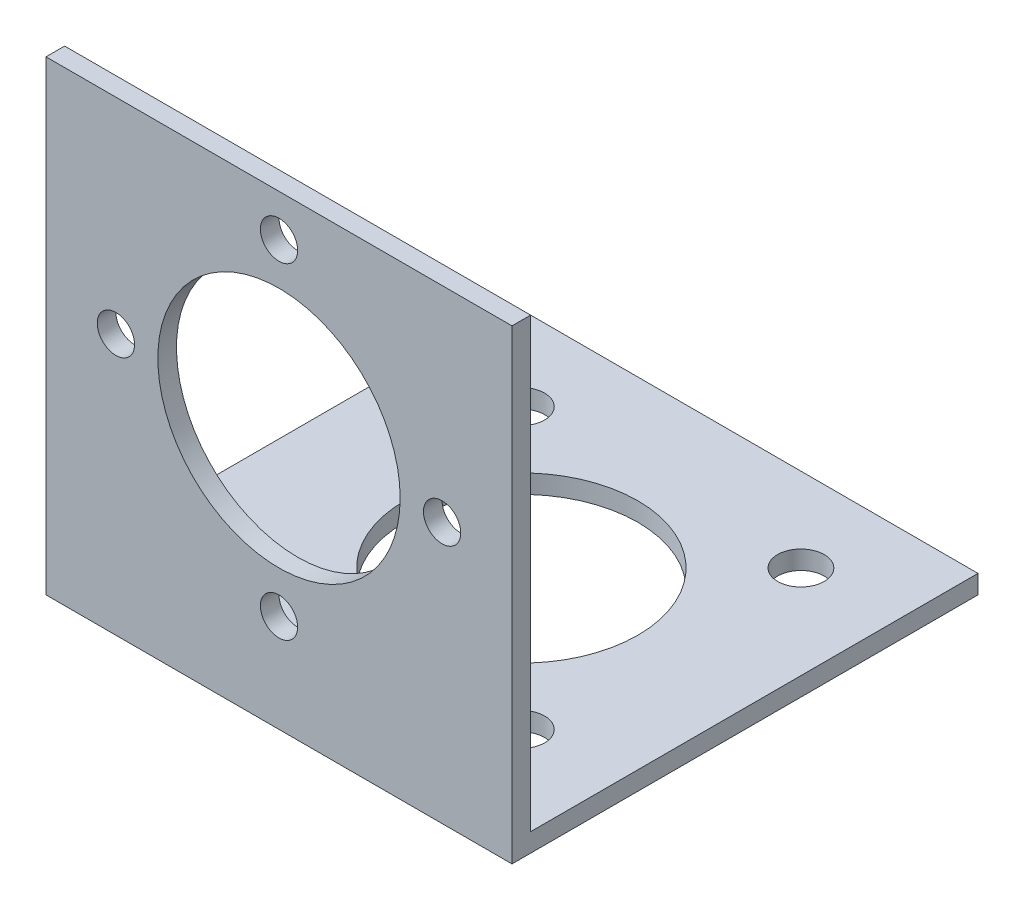
SolidWorks part; units mm, degrees
ref_plane "前视基准面" through (0, 0, 0) normal (0, 0, 1) x (1, 0, 0)
ref_plane "上视基准面" through (0, 0, 0) normal (0, 1, 0) x (1, 0, 0)
ref_plane "右视基准面" through (0, 0, 0) normal (1, 0, 0) x (0, 0, -1)
other "Configuration Table"
sketch "草图1" plane through (0, 0, 0) normal (1, 0, 0) x (0, 0, -1)
  line L0 (0, 50) -> (0, 0)
  line L1 (0, 0) -> (50, 0)
  line L2 (50, 0) -> (50, 2)
  line L3 (50, 2) -> (2, 2)
  line L4 (2, 2) -> (2, 50)
  line L5 (2, 50) -> (0, 50)
  point P3 (2, 2)
  point P8 (1.9357, 49.4968)
  dimension "D1" = 50
  dimension "D2" = 50
  dimension "D3" = 2
  dimension "D4" = 2
extrude "凸台-拉伸1" add sketch "草图1" along normal blind 50
sketch "草图2" plane through (0, 0, 0) normal (0, 0, 1) x (1, 0, 0)
  line L1 (25, 0) -> (25, 29.4445) construction
  line L2 (50, 0) -> (0, 0) construction
  line L3 (42.5, 28) -> (25, 28) construction
  line L4 (25, 28) -> (7.5, 28) construction
  line L5 (42.5, 28) -> (7.5, 28) construction
  line L6 (25, 45.5) -> (25, 10.5) construction
  circle A0 centre (25, 28) radius 13
  circle A1 centre (7.5, 28) radius 2
  circle A2 centre (25, 45.5) radius 2
  circle A3 centre (25, 10.5) radius 2
  circle A4 centre (42.5, 28) radius 2
  point P6 (25, 0)
  point P15 (25, 14.664)
  point P16 (25, 28)
  point P17 (25, 28)
  dimension "D2" = 26
  dimension "D3" = 4
  dimension "D1" = 28
  dimension "D4" = 35
  dimension "D5" = 35
extrude "切除-拉伸1" cut sketch "草图2" against normal blind 50
sketch "草图3" plane through (0, 2, 0) normal (0, 1, 0) x (1, 0, 0)
  line L0 (50, 0) -> (0, 0) construction
  line L1 (50, 50) -> (50, 2) construction
  line L2 (40, 41) -> (10, 41) construction
  line L3 (10, 41) -> (10, 11) construction
  line L4 (10, 11) -> (40, 11) construction
  line L5 (40, 11) -> (40, 41) construction
  line L6 (40, 26) -> (25, 26) construction
  line L7 (25, 11) -> (25, 26) construction
  circle A0 centre (25, 26) radius 12.5
  circle A1 centre (40, 41) radius 2.5
  circle A2 centre (40, 11) radius 2.5
  circle A3 centre (10, 41) radius 2.5
  circle A4 centre (10, 11) radius 2.5
  dimension "D1" = 25
  dimension "D4" = 5
  dimension "D2" = 26
  dimension "D3" = 25
  dimension "D5" = 30
  dimension "D6" = 30
extrude "切除-拉伸2" cut sketch "草图3" against normal blind 50
